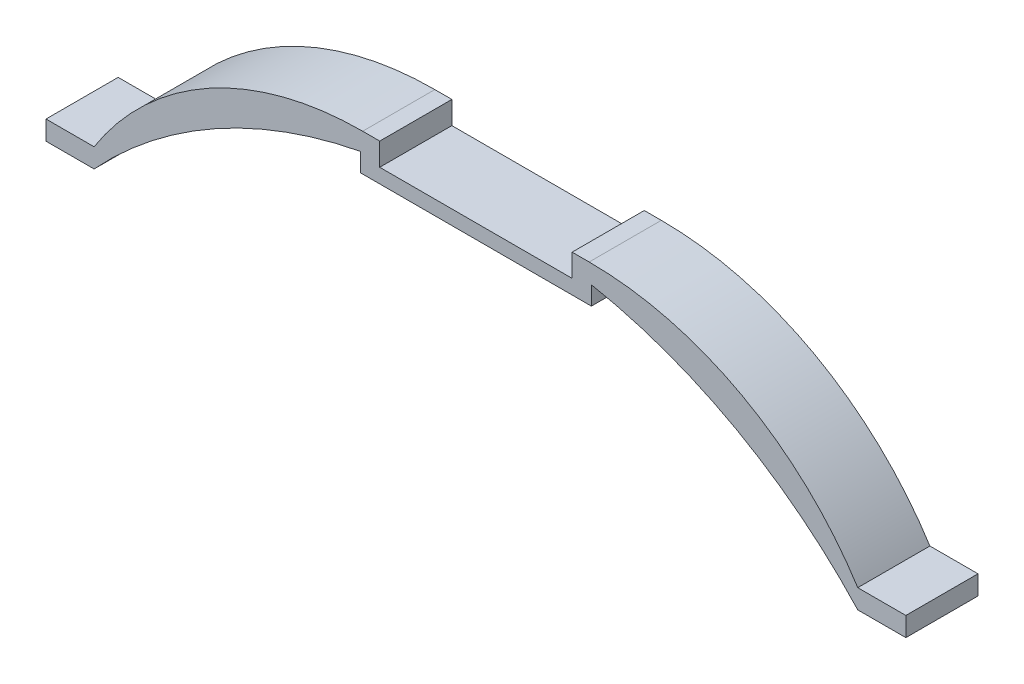
SolidWorks part; units mm, degrees
ref_plane "前基準面" through (0, 0, 0) normal (0, 0, 1) x (1, 0, 0)
ref_plane "上基準面" through (0, 0, 0) normal (0, 1, 0) x (1, 0, 0)
ref_plane "右基準面" through (0, 0, 0) normal (1, 0, 0) x (0, 0, -1)
sketch "草圖1" plane through (0, 0, 0) normal (0, 0, 1) x (1, 0, 0)
  line L0 (20, -0.8592) -> (20, 3.86)
  line L1 (-24, -3.8592) -> (24, -3.8592)
  line L2 (-24, -3.8592) -> (-24, 0)
  line L3 (-23.5438, 3.86) -> (-20, 3.86)
  line L4 (24, -3.8592) -> (24, 0)
  line L5 (0, 3.8592) -> (0, -3.8592) construction
  line L6 (-20, 0) -> (20, 0) construction
  line L7 (-20, -0.8592) -> (-20, 3.86)
  line L8 (20, -0.8592) -> (-20, -0.8592)
  line L12 (89.3823, -30.8592) -> (79.3823, -30.8592)
  line L13 (24, -0.14) -> (26.1926, -0.14) construction
  line L14 (-89.3823, -30.8592) -> (-79.3823, -30.8592)
  line L15 (-89.3823, -30.8592) -> (-89.3823, -26.8592)
  line L16 (-79.3823, -26.8592) -> (-89.3823, -26.8592)
  line L17 (20, 3.86) -> (23.5438, 3.86)
  line L18 (89.3823, -30.8592) -> (89.3823, -26.8592)
  line L19 (79.3823, -26.8592) -> (89.3823, -26.8592)
  arc A3 (-23.5438, 3.86) -> (-79.3823, -26.8592) centre (-23.5438, -62.2485) ccw
  arc A4 (-24, 0) -> (-79.3823, -30.8592) centre (-4.8327, -99.5253) ccw
  arc A5 (24, 0) -> (79.3823, -30.8592) centre (4.8327, -99.5253) cw
  arc A6 (23.5438, 3.86) -> (79.3823, -26.8592) centre (23.5438, -62.2485) cw
  point P0 (0, 0)
  dimension "D1" = 4
  dimension "D2" = 40
  dimension "D3" = 3
  dimension "D4" = 10
  dimension "D5" = 4
  dimension "D6" = 27
  dimension "D7" = 10
extrude "填料-伸長2" add sketch "草圖1" along normal blind 15 contours L14 A4 L2 L1 L4 A5 L12 L18 L19 A6 L17 L0 L8 L7 L3 A3 L16 L15
